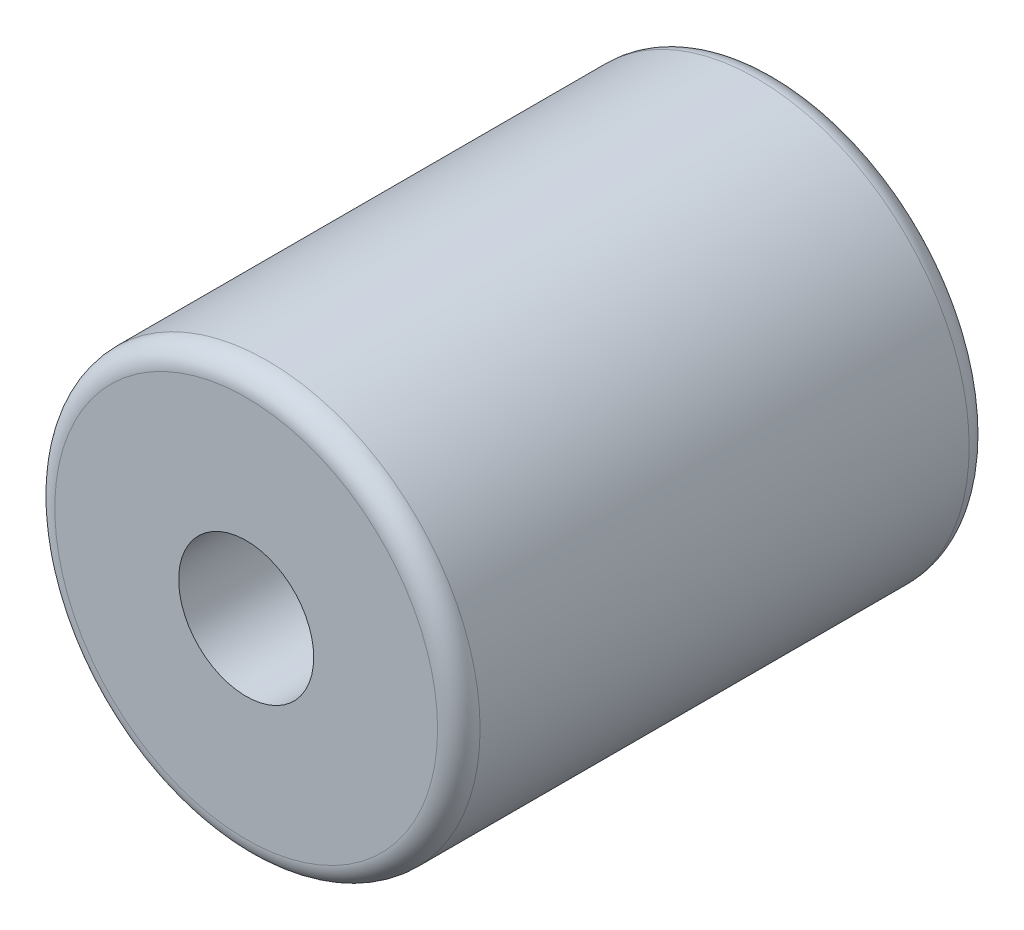
SolidWorks part; units mm, degrees
ref_plane "前视基准面" through (0, 0, 0) normal (0, 0, 1) x (1, 0, 0)
ref_plane "上视基准面" through (0, 0, 0) normal (0, 1, 0) x (1, 0, 0)
ref_plane "右视基准面" through (0, 0, 0) normal (1, 0, 0) x (0, 0, -1)
sketch "草图1" plane through (0, 0, 0) normal (0, 0, 1) x (1, 0, 0)
  circle A0 centre (0, 0) radius 3.175
  circle A1 centre (0, 0) radius 10
  dimension "D1" = 6.35
  dimension "D2" = 20
extrude "凸台-拉伸1" add sketch "草图1" along normal blind 25
fillet "圆角2" radius 1 2 edges at (10, 0, 0) (10, 0, 25)
